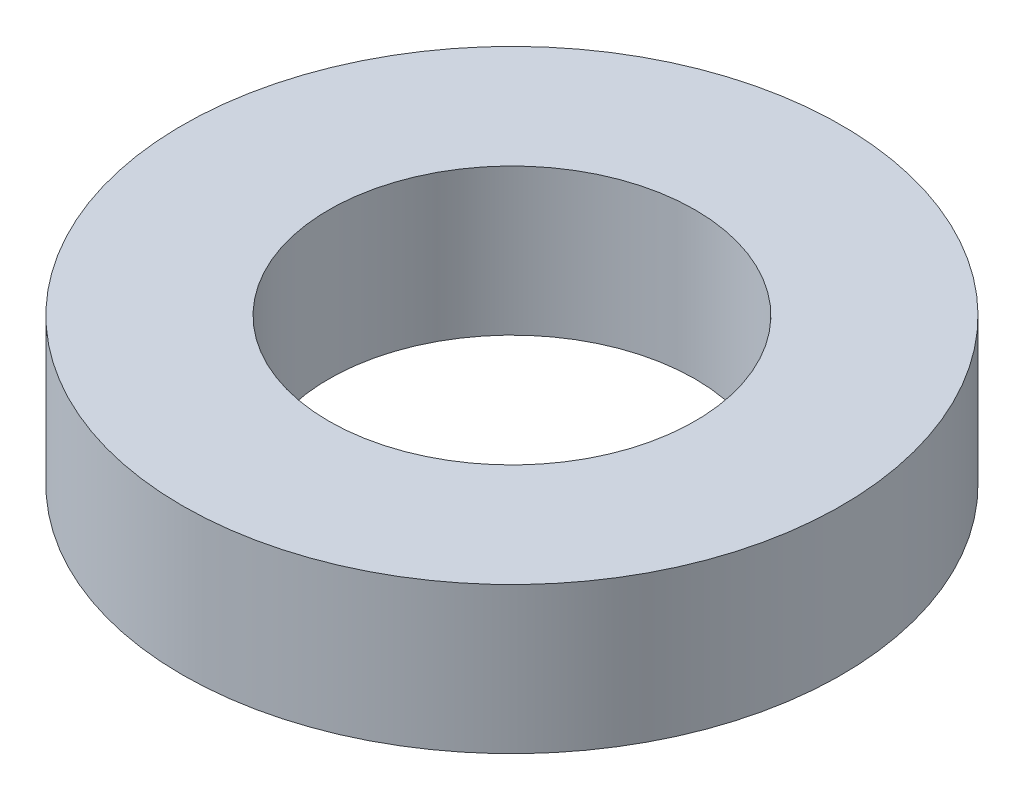
SolidWorks part; units mm, degrees
ref_plane "Front" through (0, 0, 0) normal (0, 0, 1) x (1, 0, 0)
ref_plane "Top" through (0, 0, 0) normal (0, 1, 0) x (1, 0, 0)
ref_plane "Right" through (0, 0, 0) normal (1, 0, 0) x (0, 0, -1)
sketch "Sketch1" plane through (0, 0, 0) normal (0, 1, 0) x (1, 0, 0)
  line L0 (-2.5, 0) -> (-4.5, 0) construction
  circle A0 centre (0, 0) radius 2.5
  circle A1 centre (0, 0) radius 4.5
  dimension "D1" = 5
  dimension "D2" = 9
extrude "Boss-Extrude1" add sketch "Sketch1" along normal blind 2
